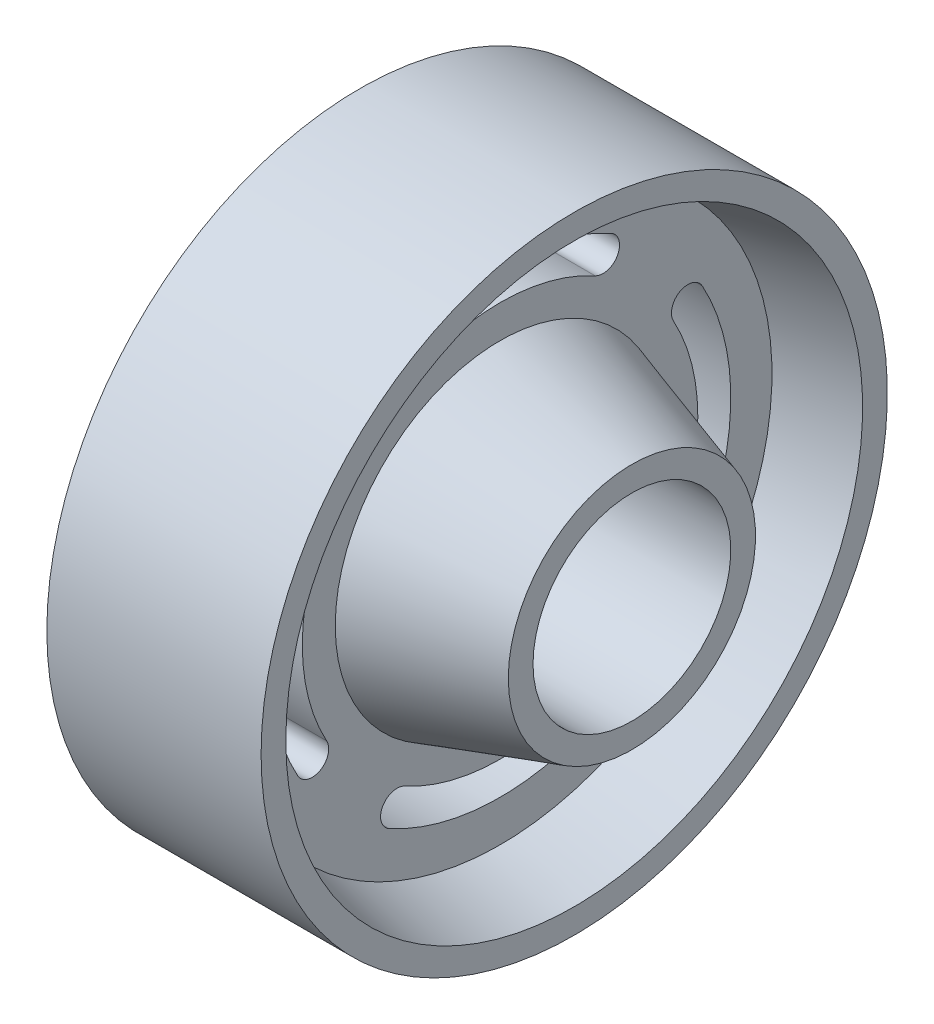
SolidWorks part; units mm, degrees
ref_plane "Front Plane" through (0, 0, 0) normal (0, 0, 1) x (1, 0, 0)
ref_plane "Top Plane" through (0, 0, 0) normal (0, 1, 0) x (1, 0, 0)
ref_plane "Right Plane" through (0, 0, 0) normal (1, 0, 0) x (0, 0, -1)
sketch "Sketch1" plane through (0, 0, 0) normal (0, 0, 1) x (1, 0, 0)
  line L0 (0, 0) -> (0, 22500.7297) construction
  line L1 (0, 0) -> (22500.7297, 0) construction
  line L2 (-13, 38) -> (13, 38)
  line L3 (-13, 38) -> (-13, 35)
  line L4 (-13, 35) -> (-4, 33)
  line L5 (-4, 33) -> (-4, 20)
  line L6 (-4, 20) -> (-20, 15)
  line L7 (-20, 15) -> (-20, 12)
  line L8 (-20, 12) -> (20, 12)
  line L9 (20, 15) -> (20, 12)
  line L10 (4, 20) -> (20, 15)
  line L11 (4, 33) -> (4, 20)
  line L12 (13, 35) -> (4, 33)
  line L13 (13, 38) -> (13, 35)
  point P15 (0, 12)
  dimension "D1" = 26
  dimension "D2" = 76
  dimension "D3" = 70
  dimension "D4" = 66
  dimension "D5" = 8
  dimension "D6" = 40
  dimension "D7" = 30
  dimension "D8" = 24
  dimension "D9" = 40
revolve "Revolve1" add sketch "Sketch1" angle 360 about L1
sketch "Sketch2" plane through (-4, 0, 0) normal (-1, 0, 0) x (0, 0, 1)
  line L0 (0, 0) -> (0, 9.386) construction
  arc A0 (-12.5, 22.798) -> (12.5, 22.798) centre (0, 0) cw construction
  arc A1 (13.4615, 24.5517) -> (-13.4615, 24.5517) centre (0, 0) ccw
  arc A2 (11.5385, 21.0443) -> (-11.5385, 21.0443) centre (0, 0) ccw
  arc A3 (11.5385, 21.0443) -> (13.4615, 24.5517) centre (12.5, 22.798) ccw
  arc A4 (-13.4615, 24.5517) -> (-11.5385, 21.0443) centre (-12.5, 22.798) ccw
  point P3 (0, 26)
  dimension "D1" = 2
  dimension "D3" = 26
  dimension "D2" = 25
extrude "Cut-Extrude1" cut sketch "Sketch2" against normal through all both and the other way through all
pattern_circular "CirPattern1" count 4 over 360 about axis through (0, 0, 0) along (1, 0, 0) of "Cut-Extrude1"
